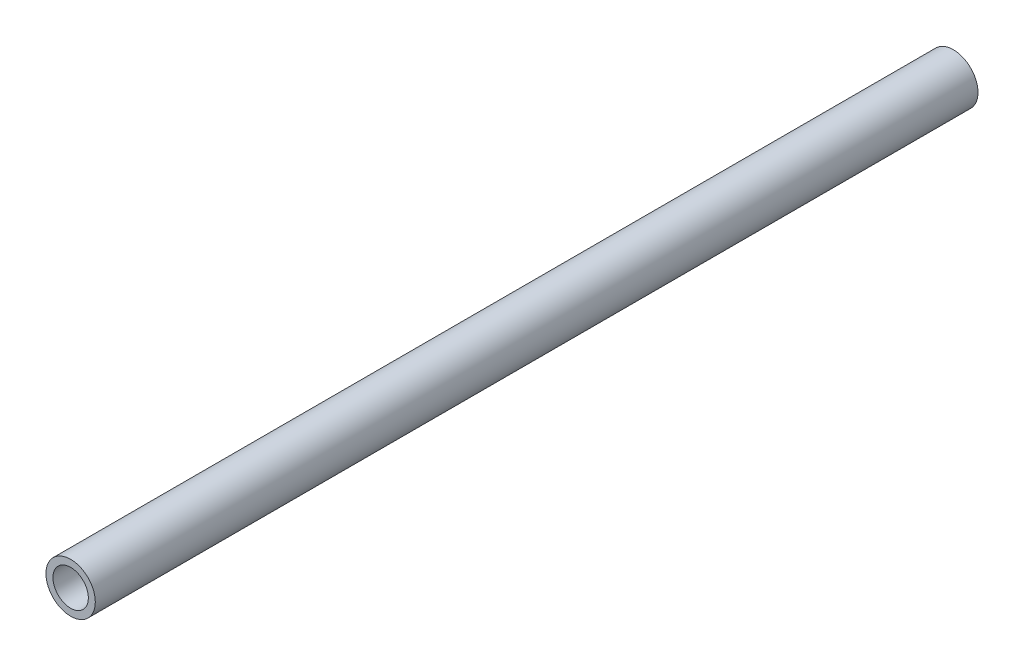
SolidWorks part; units mm, degrees
material "AISI 1020"
ref_plane "Plan de face" through (0, 0, 0) normal (0, 0, 1) x (1, 0, 0)
ref_plane "Plan de dessus" through (0, 0, 0) normal (0, 1, 0) x (1, 0, 0)
ref_plane "Plan de droite" through (0, 0, 0) normal (1, 0, 0) x (0, 0, -1)
sketch "Esquisse1" plane through (0, 0, 0) normal (0, 0, 1) x (1, 0, 0)
  circle A0 centre (0, 0) radius 4.25
  circle A1 centre (0, 0) radius 3.05
  dimension "D1" = 8.5
  dimension "D2" = 1.2
extrude "Boss.-Extru.1" add sketch "Esquisse1" along normal blind 152
sketch "Esquisse2" plane through (0, 0, 152) normal (0, 0, 1) x (1, 0, 0)
  circle A0 centre (0, 0) radius 4
  dimension "D1" = 8
extrude "Boss.-Extru.2" [suppressed] add sketch "Esquisse2" along normal blind 149.1
